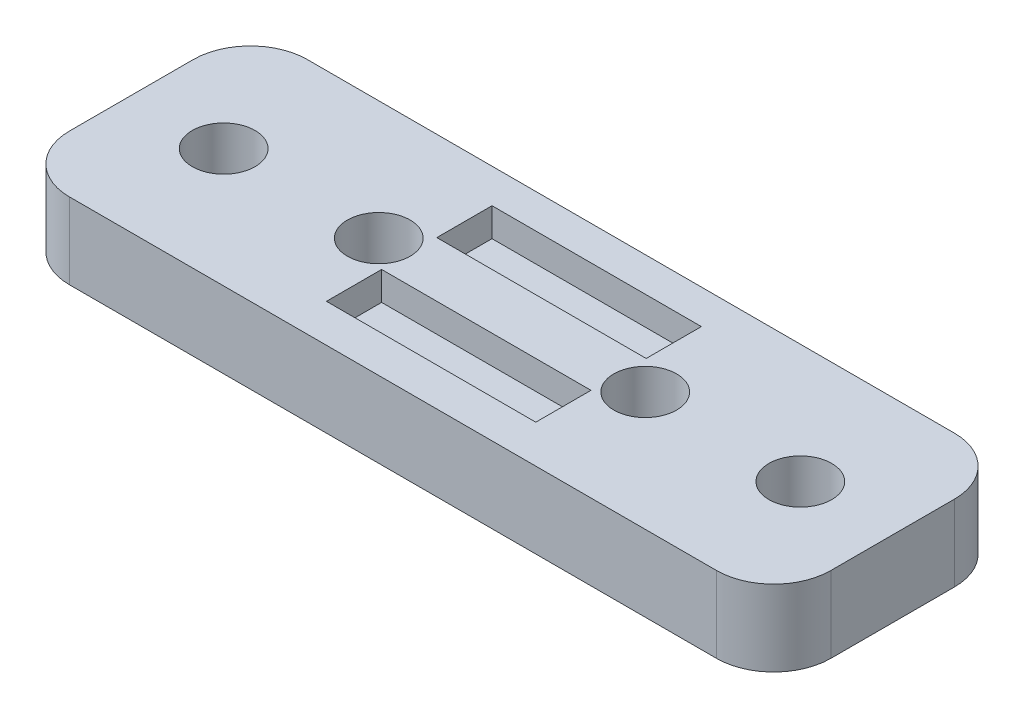
SolidWorks part; units mm, degrees
ref_plane "Front Plane" through (0, 0, 0) normal (0, 0, 1) x (1, 0, 0)
ref_plane "Top Plane" through (0, 0, 0) normal (0, 1, 0) x (1, 0, 0)
ref_plane "Right Plane" through (0, 0, 0) normal (1, 0, 0) x (0, 0, -1)
sketch "Sketch1" plane through (0, 0, 0) normal (0, 1, 0) x (1, 0, 0)
  line L1 (0, 0) -> (40, 0)
  line L2 (0, 0) -> (0, -12.5)
  line L3 (0, -12.5) -> (40, -12.5)
  line L4 (40, 0) -> (40, -12.5)
  dimension "D1" = 12.5
  dimension "D2" = 40
extrude "Boss-Extrude1" add sketch "Sketch1" along normal blind 4
sketch "Sketch2" plane through (0, 4, 0) normal (0, 1, 0) x (1, 0, 0)
  line L0 (0, 0) -> (0, -12.5) construction
  line L1 (40, 0) -> (0, 0) construction
  circle A0 centre (4.85, -6.25) radius 1.65
  circle A1 centre (13, -6.25) radius 1.65
  circle A2 centre (27, -6.25) radius 1.65
  circle A3 centre (35.15, -6.25) radius 1.65
  dimension "D1" = 3.3
  dimension "D4" = 4.85
  dimension "D5" = 6.25
  dimension "D2" = 2
  dimension "D3" = 2
extrude "Cut-Extrude1" cut sketch "Sketch2" against normal through all
sketch "Sketch3" plane through (0, 4, 0) normal (0, 1, 0) x (1, 0, 0)
  line L0 (0, 0) -> (0, -12.5) construction
  line L1 (14.5, -1.8) -> (25.5, -1.8)
  line L2 (14.5, -1.8) -> (14.5, -4.7)
  line L3 (14.5, -4.7) -> (25.5, -4.7)
  line L4 (25.5, -1.8) -> (25.5, -4.7)
  line L5 (40, 0) -> (0, 0) construction
  line L6 (14.5, -10.5) -> (25.5, -10.5)
  line L7 (14.5, -7.6) -> (14.5, -10.5)
  line L8 (14.5, -7.6) -> (25.5, -7.6)
  line L9 (25.5, -7.6) -> (25.5, -10.5)
  dimension "D1" = 2.9
  dimension "D2" = 11
  dimension "D3" = 14.5
  dimension "D4" = 1.8
  dimension "D5" = 2
extrude "Cut-Extrude2" cut sketch "Sketch3" against normal blind 1.5
fillet "Fillet1" radius 3 4 edges at (40, 2, 0) (40, 2, 12.5) (0, 2, 12.5) (0, 2, 0)
equation "\"滑动-垂直孔\"= 0.6"
equation "\"滑动-水平孔\"= 0.3"
equation "\"松动-垂直孔\"= 0.3"
equation "\"松动-水平孔\"= 0.1"
equation "\"正常-垂直孔\"= 0.15"
equation "\"正常-水平孔\"= 0"
equation "\"紧缩-垂直孔\"= 0"
equation "\"紧缩-水平孔\"= - 0.1"
equation "\"D1@Sketch2\"=\"松动-垂直孔\"+3"
equation "\"D4@Sketch2\"=\"D2@Sketch1\"/2-14/2-8.15"
equation "\"D5@Sketch2\"=\"D1@Sketch1\"/2"
equation "\"D3@Sketch3\"=\"D2@Sketch1\"/2-\"D2@Sketch3\"/2"
equation "\"D1@Sketch3\"=5.8/2"
